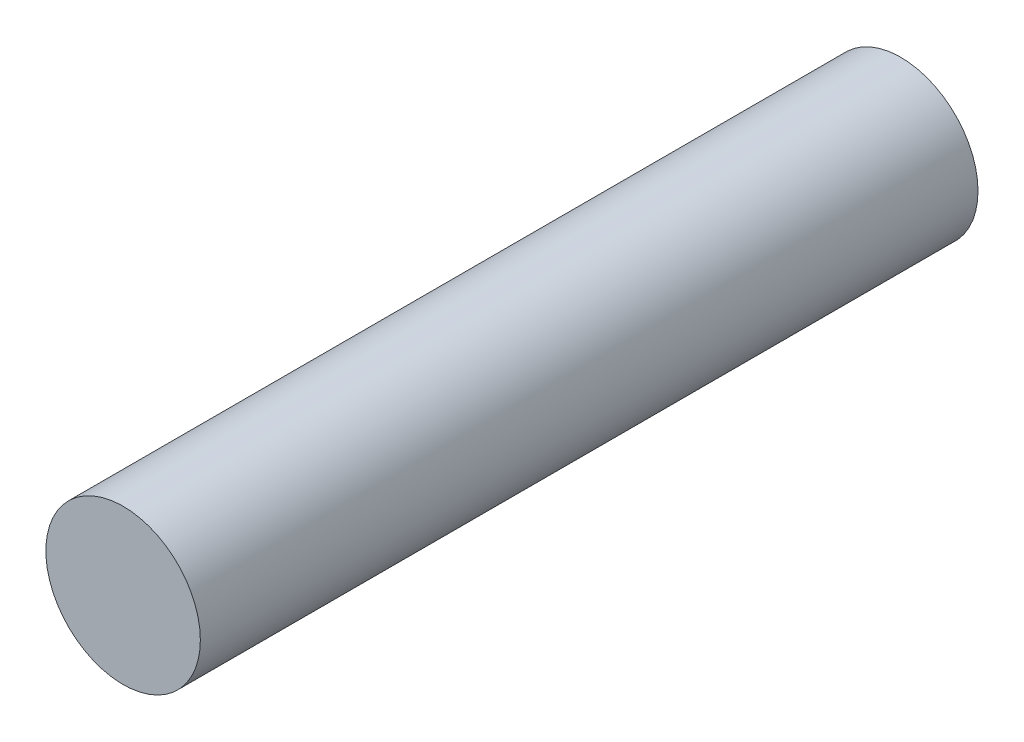
SolidWorks part; units mm, degrees
ref_plane "前视基准面" through (0, 0, 0) normal (0, 0, 1) x (1, 0, 0)
ref_plane "上视基准面" through (0, 0, 0) normal (0, 1, 0) x (1, 0, 0)
ref_plane "右视基准面" through (0, 0, 0) normal (1, 0, 0) x (0, 0, -1)
other "Configuration Table"
sketch "草图1" plane through (0, 0, 0) normal (0, 0, 1) x (1, 0, 0)
  circle A0 centre (0, 0) radius 1.49
  dimension "D1" = 2.98
extrude "凸台-拉伸1" add sketch "草图1" along normal blind 15
